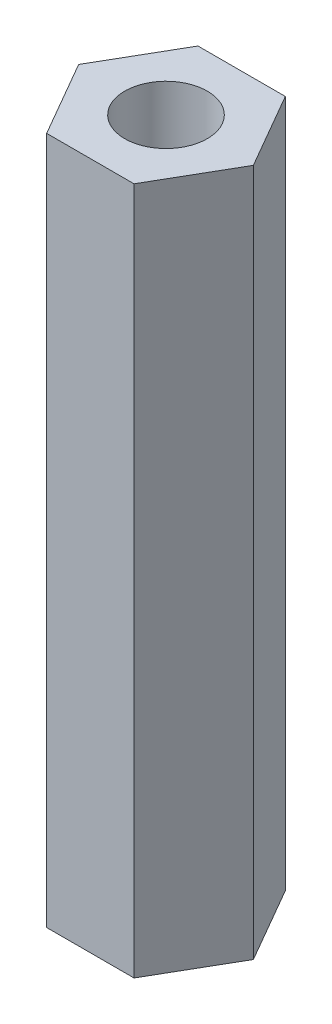
SolidWorks part; units mm, degrees
ref_plane "Front Plane" through (0, 0, 0) normal (0, 0, 1) x (1, 0, 0)
ref_plane "Top Plane" through (0, 0, 0) normal (0, 1, 0) x (1, 0, 0)
ref_plane "Right Plane" through (0, 0, 0) normal (1, 0, 0) x (0, 0, -1)
sketch "Sketch1" plane through (0, 0, 0) normal (0, 1, 0) x (1, 0, 0)
  line L1 (3.1754, 0) -> (1.5877, 2.75)
  line L2 (1.5877, 2.75) -> (-1.5877, 2.75)
  line L3 (-1.5877, 2.75) -> (-3.1754, 0)
  line L4 (-3.1754, 0) -> (-1.5877, -2.75)
  line L5 (-1.5877, -2.75) -> (1.5877, -2.75)
  line L6 (1.5877, -2.75) -> (3.1754, 0)
  circle A0 centre (0, 0) radius 2.75 construction
  dimension "D1" = 5.5
extrude "Boss-Extrude1" add sketch "Sketch1" along normal blind 25
sketch "Sketch2" plane through (0, 25, 0) normal (0, 1, 0) x (1, 0, 0)
  circle A0 centre (0, 0) radius 1.5
  dimension "D1" = 3
extrude "Cut-Extrude1" cut sketch "Sketch2" against normal blind 10
ref_plane "Plane1" through (0, 12.5, 0) normal (0, -1, 0) x (-1, 0, 0)
mirror "Mirror1" about plane through (0, 12.5, 0) normal (0, -1, 0) of "Cut-Extrude1"
